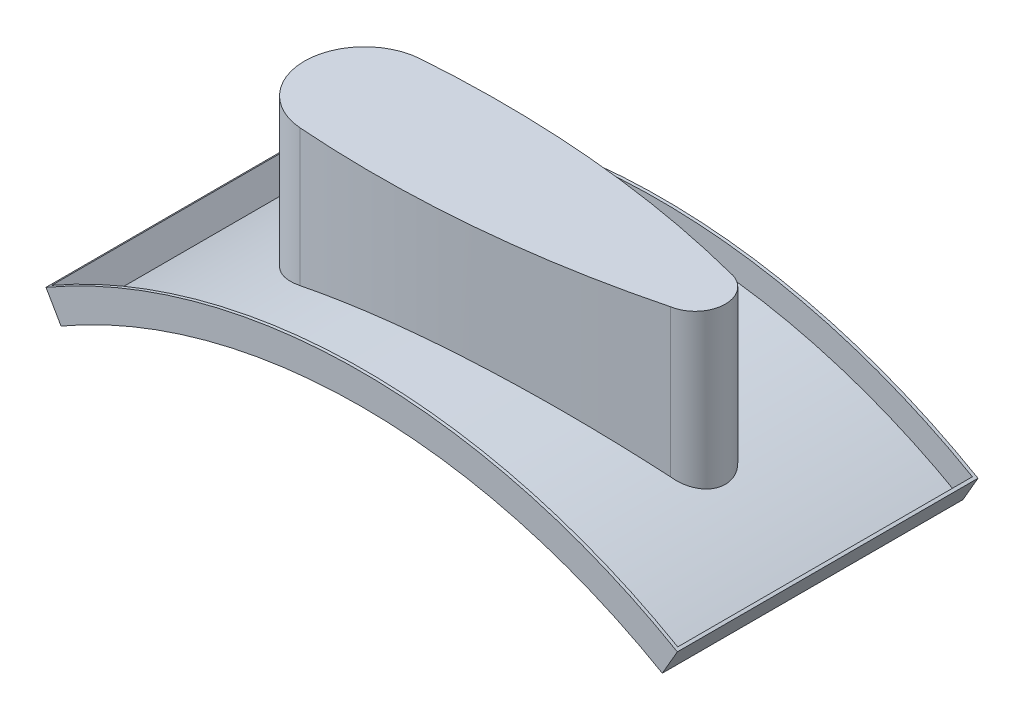
SolidWorks part; units mm, degrees
ref_plane "Front Plane" through (0, 0, 0) normal (0, 0, 1) x (1, 0, 0)
ref_plane "Top Plane" through (0, 0, 0) normal (0, 1, 0) x (1, 0, 0)
ref_plane "Right Plane" through (0, 0, 0) normal (1, 0, 0) x (0, 0, -1)
sketch "Sketch1" plane through (0, 0, 0) normal (0, 0, 1) x (1, 0, 0)
  line L0 (0, 0) -> (0, 144270.1258) construction
  line L1 (0, 0) -> (-144270.1258, 0) construction
  line L3 (-105, 181.8653) -> (-100, 173.2051)
  line L4 (105, 181.8653) -> (100, 173.2051)
  arc A1 (100, 173.2051) -> (-100, 173.2051) centre (0, 0) ccw
  arc A2 (105, 181.8653) -> (-105, 181.8653) centre (0, 0) ccw
  dimension "D1" = 10
  dimension "D2" = 200
extrude "Boss-Extrude1" add sketch "Sketch1" along normal blind 100
ref_plane "Plane1" through (0, 0, 1) normal (0, 0, -1) x (-1, 0, 0)
sketch "Sketch2" plane through (0, 0, 1) normal (0, 0, -1) x (-1, 0, 0)
  line L0 (-103.6328, 181.4972) -> (-99.6327, 174.569)
  line L1 (99.6327, 174.569) -> (103.6328, 181.4972)
  line L2 (100, 173.2051) -> (105, 181.8653)
  line L3 (-105, 181.8653) -> (-100, 173.2051)
  line L4 (100, 173.2051) -> (105, 181.8653)
  line L5 (-105, 181.8653) -> (-100, 173.2051)
  line L6 (-103.6328, 181.4972) -> (-105.3592, 184.4876)
  line L7 (103.6328, 181.4972) -> (105.3592, 184.4876)
  arc A0 (99.6327, 174.569) -> (-99.6327, 174.569) centre (0, 0) ccw
  arc A1 (103.6328, 181.4972) -> (-103.6328, 181.4972) centre (0, 0) ccw
  arc A2 (100, 173.2051) -> (-100, 173.2051) centre (0, 0) ccw
  arc A3 (105, 181.8653) -> (-105, 181.8653) centre (0, 0) ccw
  arc A4 (100, 173.2051) -> (-100, 173.2051) centre (0, 0) ccw
  arc A5 (105, 181.8653) -> (-105, 181.8653) centre (0, 0) ccw
  arc A6 (-105.3592, 184.4876) -> (105.3592, 184.4876) centre (0, 7.5128) cw
  dimension "D1" = 0
  dimension "D2" = 1
extrude "Cut-Extrude1" cut sketch "Sketch2" against normal blind 98 contours L1 A1 L0 A0 | L7 A5 L6 A1 | A6 L6 A5 L7
sketch "Sketch3" plane through (0, 0, 0) normal (0, 1, 0) x (1, 0, 0)
  line L0 (-49.0526, -50) -> (60.9474, -50) construction
  arc A0 (-50.5336, -30.0549) -> (-50.5336, -69.9451) centre (-49.0526, -50) ccw
  arc A1 (62.6351, -59.8566) -> (62.6351, -40.1434) centre (60.9474, -50) ccw
  arc A2 (-50.5336, -30.0549) -> (62.6351, -40.1434) centre (-24.615, -379.0939) cw
  arc A3 (-50.5336, -69.9451) -> (62.6351, -59.8566) centre (-24.615, 279.0939) ccw
  point P1 (-69.0526, -50)
  point P3 (70.9474, -50)
  dimension "D1" = 40
  dimension "D2" = 20
  dimension "D3" = 350
  dimension "D4" = 140
extrude "Boss-Extrude2" add sketch "Sketch3" along normal blind 240
sketch "Sketch4" plane through (0, 0, 0) normal (0, 0, 1) x (1, 0, 0)
  line L0 (-69.0526, 187.7012) -> (-69.0526, 0) construction
  line L1 (70.9474, 0) -> (70.9474, 186.9932) construction
  line L2 (-69.0526, 187.7012) -> (-109.0278, 39.1691)
  line L3 (-109.0278, 39.1691) -> (-56.1066, -33.4678)
  line L4 (-56.1066, -33.4678) -> (100.0627, -27.7607)
  line L5 (100.0627, -27.7607) -> (70.9474, 186.9932)
  arc A0 (-69.0526, 187.7012) -> (70.9474, 186.9932) centre (0, 0) cw
  arc A1 (100, 173.2051) -> (-100, 173.2051) centre (0, 0) ccw construction
extrude "Cut-Extrude2" cut sketch "Sketch4" along normal blind 305
